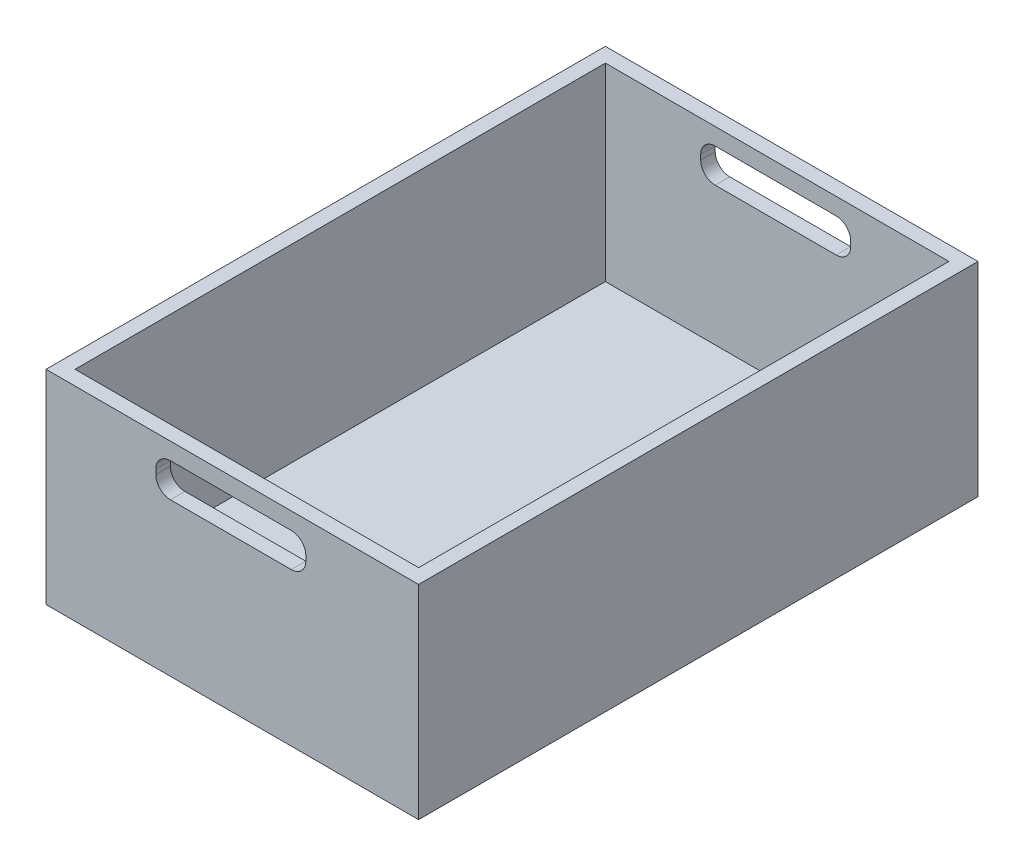
SolidWorks part; units mm, degrees
ref_plane "Front Plane" through (0, 0, 0) normal (0, 0, 1) x (1, 0, 0)
ref_plane "Top Plane" through (0, 0, 0) normal (0, 1, 0) x (1, 0, 0)
ref_plane "Right Plane" through (0, 0, 0) normal (1, 0, 0) x (0, 0, -1)
sketch "Sketch1" plane through (0, 0, 0) normal (0, 1, 0) x (1, 0, 0)
  line L1 (-192.5, -289) -> (192.5, -289)
  line L2 (-192.5, -289) -> (-192.5, 289)
  line L3 (-192.5, 289) -> (192.5, 289)
  line L4 (192.5, -289) -> (192.5, 289)
  line L5 (-192.5, -289) -> (192.5, 289) construction
  line L6 (-192.5, 289) -> (192.5, -289) construction
  point P0 (0, 0)
  dimension "D1" = 385
  dimension "D2" = 578
extrude "Boss-Extrude1" add sketch "Sketch1" along normal blind 15
sketch "Sketch2" plane through (0, 15, 0) normal (0, 1, 0) x (1, 0, 0)
  line L0 (192.5, 289) -> (-192.5, 289) construction
  line L1 (192.5, -289) -> (177.5, -289)
  line L2 (192.5, -289) -> (192.5, 289)
  line L3 (192.5, 289) -> (177.5, 289)
  line L4 (177.5, -289) -> (177.5, 289)
  dimension "D1" = 15
extrude "Boss-Extrude2" add sketch "Sketch2" along normal blind 195.5
mirror "Mirror1" about plane through (0, 0, 0) normal (1, 0, 0) of "Boss-Extrude2"
sketch "Sketch3" plane through (0, 15, 0) normal (0, 1, 0) x (1, 0, 0)
  line L0 (177.5, 289) -> (177.5, -289) construction
  line L1 (-177.5, -289) -> (177.5, -289)
  line L2 (-177.5, -289) -> (-177.5, -274)
  line L3 (-177.5, -274) -> (177.5, -274)
  line L4 (177.5, -289) -> (177.5, -274)
  dimension "D1" = 15
extrude "Boss-Extrude3" add sketch "Sketch3" along normal blind 195.5
mirror "Mirror2" about plane through (0, 0, 0) normal (0, 0, 1) of "Boss-Extrude3"
sketch "Sketch4" plane through (0, 0, 289) normal (0, 0, 1) x (1, 0, 0)
  line L1 (-64.0344, 193) -> (60.9656, 193)
  line L2 (-79.0344, 178) -> (-79.0344, 173)
  line L3 (-64.0344, 158) -> (60.9656, 158)
  line L4 (75.9656, 178) -> (75.9656, 173)
  line L5 (-79.0344, 193) -> (75.9656, 158) construction
  line L6 (-79.0344, 158) -> (75.9656, 193) construction
  line L7 (-192.5, 210.5) -> (192.5, 210.5) construction
  arc A0 (60.9656, 193) -> (75.9656, 178) centre (60.9656, 178) cw
  arc A1 (60.9656, 158) -> (75.9656, 173) centre (60.9656, 173) ccw
  arc A2 (-79.0344, 173) -> (-64.0344, 158) centre (-64.0344, 173) ccw
  arc A3 (-64.0344, 193) -> (-79.0344, 178) centre (-64.0344, 178) ccw
  point P0 (-1.5344, 175.5)
  point P17 (0, 0)
  point P18 (0, 0)
  dimension "D1" = 35
  dimension "D2" = 125
  dimension "D3" = 5
extrude "Cut-Extrude1" cut sketch "Sketch4" against normal through all both and the other way through all
